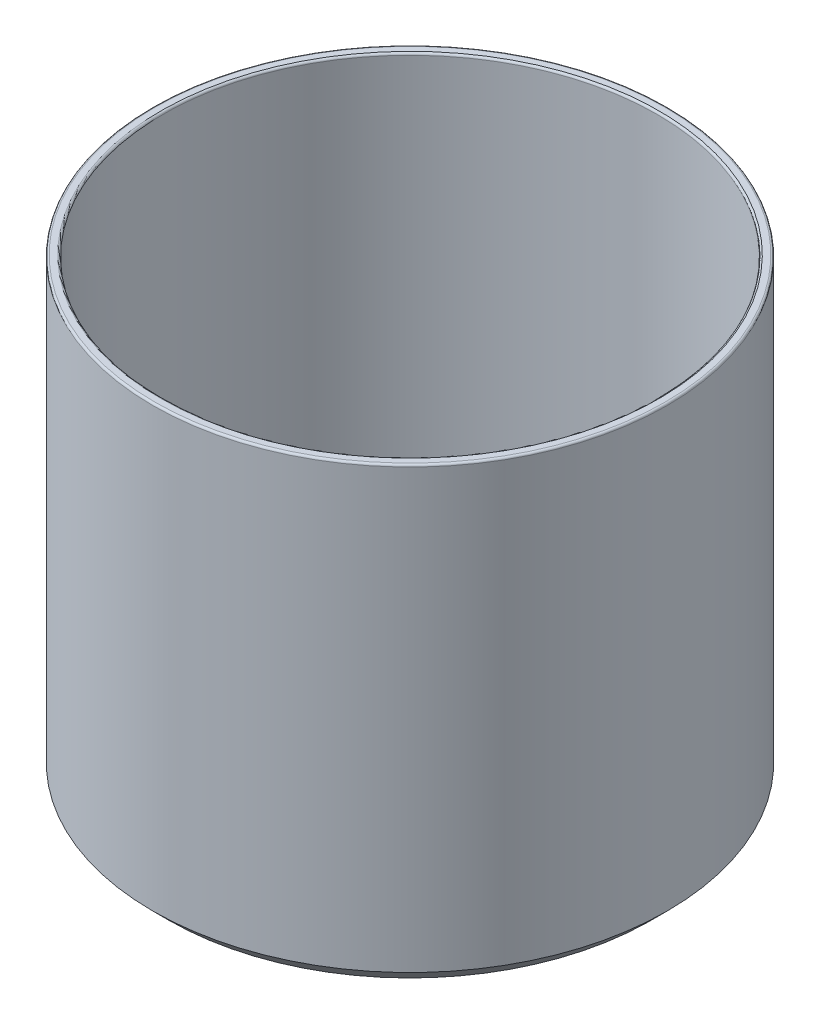
SolidWorks part; units mm, degrees
ref_plane "前视基准面" through (0, 0, 0) normal (0, 0, 1) x (1, 0, 0)
ref_plane "上视基准面" through (0, 0, 0) normal (0, 1, 0) x (1, 0, 0)
ref_plane "右视基准面" through (0, 0, 0) normal (1, 0, 0) x (0, 0, -1)
other "Configuration Table"
sketch "草图1" plane through (0, 0, 0) normal (0, 1, 0) x (1, 0, 0)
  circle A0 centre (0, 0) radius 127.5
  dimension "D1" = 255
extrude "凸台-拉伸1" add sketch "草图1" along normal blind 6
sketch "草图2" plane through (0, 6, 0) normal (0, 1, 0) x (1, 0, 0)
  circle A1 centre (0, 0) radius 122.5
  circle A2 centre (0, 0) radius 127.5
  circle A3 centre (0, 0) radius 127.5
  dimension "D1" = 0
  dimension "D2" = 5
extrude "凸台-拉伸2" add sketch "草图2" along normal blind 220
sketch "草图3" plane through (0, 6, 0) normal (0, 1, 0) x (1, 0, 0)
  circle A0 centre (0, 0) radius 10
  dimension "D1" = 20
extrude "切除-拉伸1" cut sketch "草图3" against normal blind 200
fillet "圆角1" radius 10 1 edges at (0, 6, 122.5)
chamfer "倒角1" distance 8 angle 45 1 edges at (0, 0, 127.5)
fillet "圆角2" radius 1 2 edges at (0, 226, 127.5) (0, 226, 122.5)
chamfer "倒角2" distance 1 angle 45 1 edges at (0, 0, 10)
fillet "圆角3" radius 1 1 edges at (0, 6, 10)
